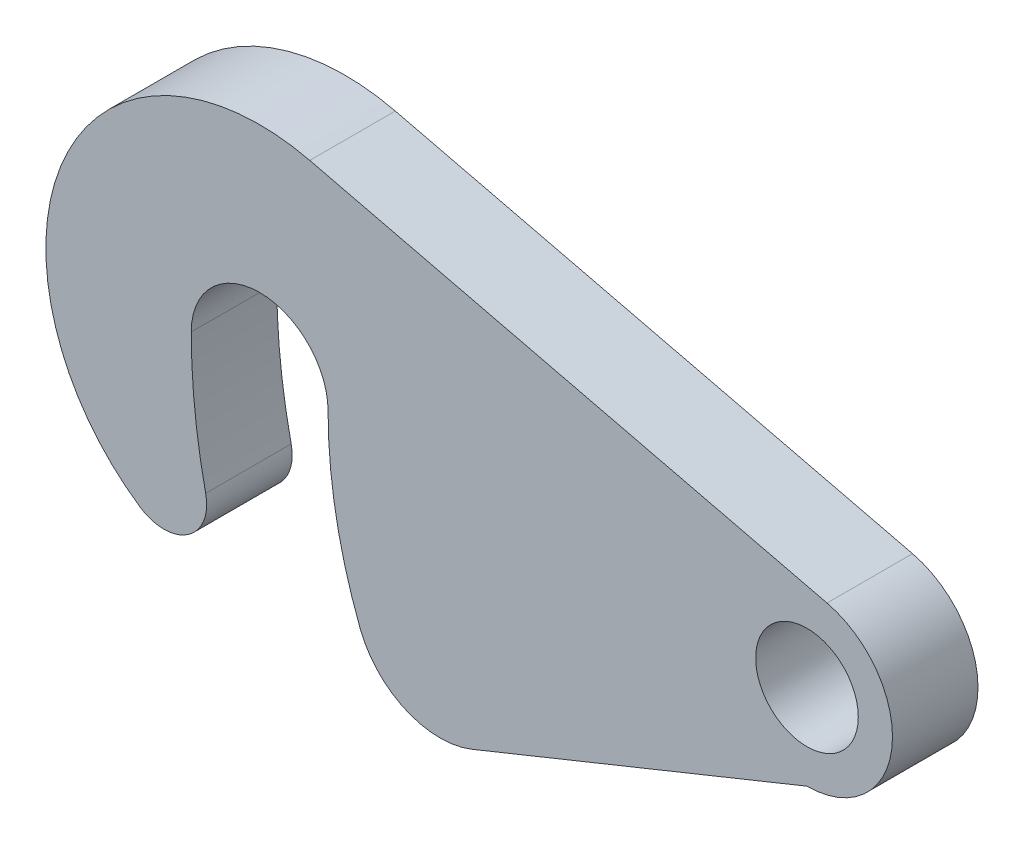
SolidWorks part; units mm, degrees
ref_plane "Front Plane" through (0, 0, 0) normal (0, 0, 1) x (1, 0, 0)
ref_plane "Top Plane" through (0, 0, 0) normal (0, 1, 0) x (1, 0, 0)
ref_plane "Right Plane" through (0, 0, 0) normal (1, 0, 0) x (0, 0, -1)
sketch "Sketch1" plane through (0, 0, 0) normal (0, 0, 1) x (1, 0, 0)
  line L0 (0, 92.9767) -> (0, -82.9498) construction
  line L1 (2.3438, 9.7215) -> (-58.1406, 24.3037)
  line L2 (0, 0) -> (-31.4559, 0) construction
  line L3 (0, -10) -> (-39.1604, -25.8431)
  circle A0 centre (0, 0) radius 6
  arc A1 (-56, 0) -> (-72, 0) centre (-64, 0) ccw
  arc A4 (-58.1406, 24.3037) -> (-77.9941, -20.7163) centre (-64, 0) ccw
  arc A5 (0, -10) -> (0, 10) centre (0, 0) ccw
  arc A6 (-56, 0) -> (-52.2392, -20.1758) centre (0, 0) ccw
  arc A7 (-72, 0) -> (-70.3125, -15.4968) centre (0, 0) ccw
  arc A8 (-70.3125, -15.4968) -> (-77.9941, -20.7163) centre (-75.1953, -16.573) cw
  arc A9 (-52.2392, -20.1758) -> (-39.1604, -25.8431) centre (-42.9108, -16.573) ccw
  point P18 (-39.5819, -25.218)
  point P20 (0, 0)
  point P21 (0, 0)
  dimension "D1" = 12
  dimension "D2" = 16
  dimension "D3" = 64
  dimension "D4" = 20
  dimension "D5" = 112
  dimension "D6" = 50
  dimension "D7" = 144
  dimension "D8" = 5
  dimension "D9" = 10
extrude "Boss-Extrude1" add sketch "Sketch1" along normal mid plane 10
